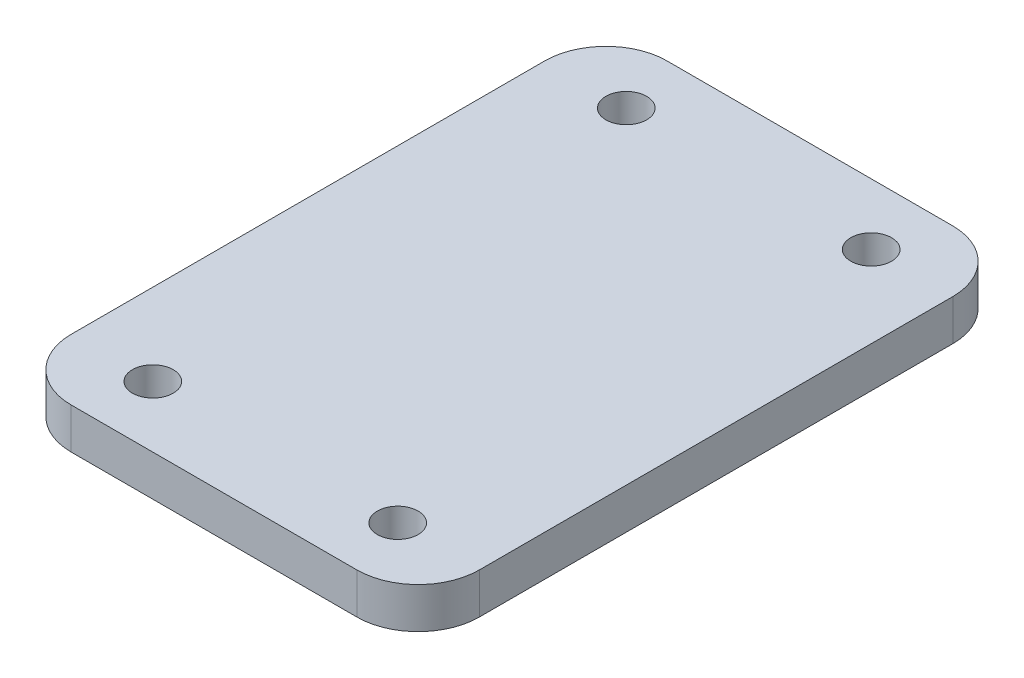
SolidWorks part; units mm, degrees
material "AISI 304"
ref_plane "Front Plane" through (0, 0, 0) normal (0, 0, 1) x (1, 0, 0)
ref_plane "Top Plane" through (0, 0, 0) normal (0, 1, 0) x (1, 0, 0)
ref_plane "Right Plane" through (0, 0, 0) normal (1, 0, 0) x (0, 0, -1)
sketch "Croquis1" plane through (0, 0, 0) normal (0, 1, 0) x (1, 0, 0)
  line L1 (50, -73) -> (-50, -73)
  line L2 (50, -73) -> (50, 73)
  line L3 (50, 73) -> (-50, 73)
  line L4 (-50, -73) -> (-50, 73)
  line L5 (50, -73) -> (-50, 73) construction
  line L6 (50, 73) -> (-50, -73) construction
  point P0 (0, 0)
  dimension "D1" = 146
  dimension "D2" = 100
extrude "Saliente-Extruir2" add sketch "Croquis1" along normal blind 10
fillet "Redondeo1" radius 15 4 edges at (-50, 5, -73) (50, 5, -73) (50, 5, 73) (-50, 5, 73)
sketch "Croquis2" plane through (0, 10, 0) normal (0, 1, 0) x (1, 0, 0)
  line L0 (-50, 58) -> (-50, -58) construction
  line L1 (-35, -73) -> (35, -73) construction
  circle A0 centre (-30, -58) radius 5
  dimension "D3" = 10
  dimension "D1" = 20
  dimension "D2" = 15
extrude "Cortar-Extruir1" cut sketch "Croquis2" against normal blind 10
pattern_linear "MatrizL1" count 2 spacing 116 along (0, 0, -1) of "Cortar-Extruir1"
pattern_linear "MatrizL2" count 2 spacing 60 along (1, 0, 0) of "MatrizL1", "Cortar-Extruir1"
